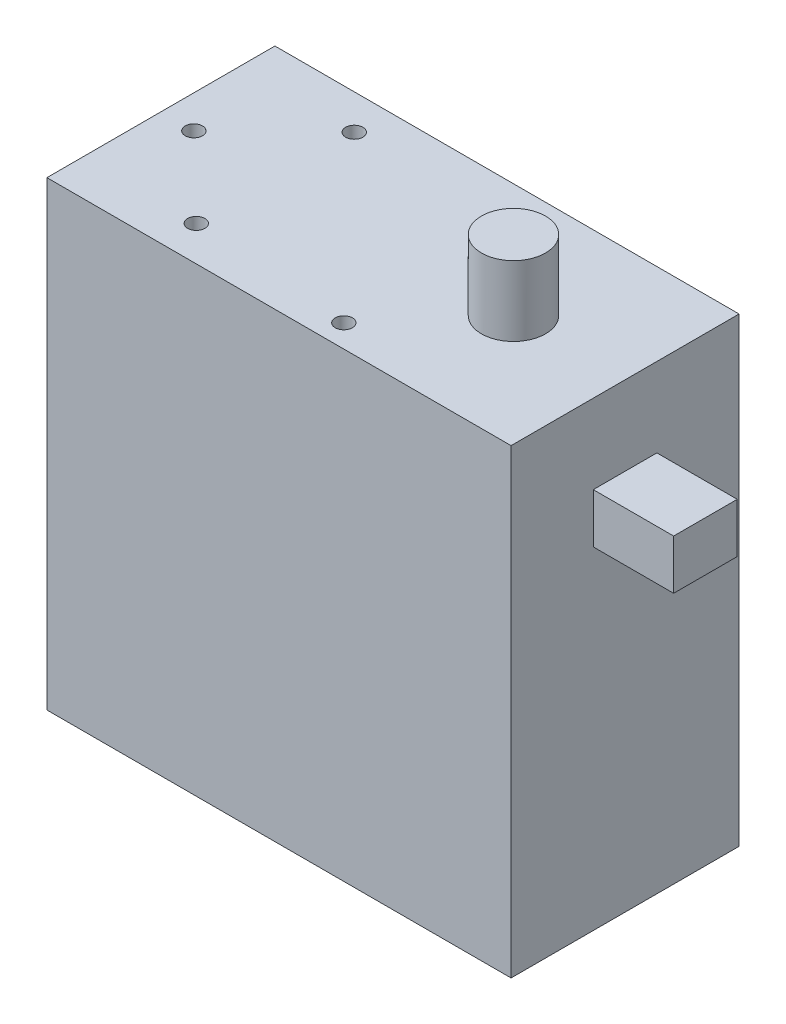
SolidWorks part; units mm, degrees
ref_plane "Front Plane" through (0, 0, 0) normal (0, 0, 1) x (1, 0, 0)
ref_plane "Top Plane" through (0, 0, 0) normal (0, 1, 0) x (1, 0, 0)
ref_plane "Right Plane" through (0, 0, 0) normal (1, 0, 0) x (0, 0, -1)
sketch "Sketch1" plane through (0, 0, 0) normal (0, 0, 1) x (1, 0, 0)
  line L1 (0, 0) -> (40.43, 0)
  line L2 (0, 0) -> (0, 40.16)
  line L3 (0, 40.16) -> (40.43, 40.16)
  line L4 (40.43, 0) -> (40.43, 40.16)
  dimension "D1" = 40.16
  dimension "D2" = 40.43
extrude "ServoBody" add sketch "Sketch1" along normal blind 19.86
sketch "Sketch2" plane through (0, 40.16, 0) normal (0, 1, 0) x (1, 0, 0)
  line L0 (40.43, -19.86) -> (40.43, 0) construction
  circle A0 centre (30.71, -9.93) radius 2.79
  point P4 (0, 0)
  point P5 (40.43, -9.93)
  dimension "D1" = 5.58
  dimension "D2" = 9.72
extrude "GearHinge" add sketch "Sketch2" along normal blind 6.1
sketch "Sketch3" plane through (0, 0, 0) normal (0, -1, 0) x (1, 0, 0)
  circle A0 centre (30.71, 9.93) radius 3.01
  circle A1 centre (30.71, 9.93) radius 2.79 construction
  dimension "D1" = 6.02
extrude "SmoothHinge" add sketch "Sketch3" along normal blind 5.5
sketch "Sketch4" plane through (0, 40.16, 0) normal (0, 1, 0) x (1, 0, 0)
  line L0 (40.43, -19.86) -> (40.43, 0) construction
  line L1 (40.43, 0) -> (0, 0) construction
  line L2 (40.43, -19.86) -> (0, -19.86) construction
  line L3 (0, -19.86) -> (0, 0) construction
  circle A0 centre (23.88, -1.98) radius 0.75
  circle A4 centre (23.88, -17.88) radius 0.75
  circle A5 centre (2.87, -9.93) radius 0.75
  circle A6 centre (9.96, -3.05) radius 0.75
  circle A7 centre (9.96, -16.81) radius 0.75
  point P14 (0, 0)
  point P15 (0, 0)
  point P18 (0, 0)
  point P21 (0, -9.93)
  dimension "D1" = 1.5
  dimension "D4" = 1.98
  dimension "D2" = 16.55
  dimension "D3" = 1.98
  dimension "D5" = 3.05
  dimension "D6" = 3.05
  dimension "D7" = 13.92
  dimension "D8" = 2.87
extrude "GearScrewHoles" cut sketch "Sketch4" against normal blind 2
sketch "Sketch5" plane through (0, 0, 0) normal (0, -1, 0) x (1, 0, 0)
  line L0 (40.43, 19.86) -> (40.43, 0) construction
  line L1 (0, 19.86) -> (40.43, 19.86) construction
  line L3 (0, 0) -> (40.43, 0) construction
  circle A0 centre (17.31, 17.86) radius 0.75
  circle A1 centre (38.43, 17.86) radius 0.75
  circle A2 centre (2.07, 17.86) radius 0.75
  circle A3 centre (17.31, 2) radius 0.75
  circle A4 centre (38.43, 2) radius 0.75
  circle A5 centre (2.07, 2) radius 0.75
  point P16 (0, 0)
  point P17 (0, 0)
  dimension "D1" = 1.5
  dimension "D2" = 21.12
  dimension "D3" = 2
  dimension "D4" = 2
  dimension "D5" = 15.24
  dimension "D6" = 2
extrude "SmoothScrewHoles" cut sketch "Sketch5" against normal blind 2
sketch "Sketch6" plane through (40.43, 0, 0) normal (1, 0, 0) x (0, 0, -1)
  line L0 (-19.86, 40.16) -> (0, 40.16) construction
  line L1 (-12.7, 33.26) -> (-7.16, 33.26)
  line L2 (-12.7, 33.26) -> (-12.7, 28.94)
  line L3 (-12.7, 28.94) -> (-7.16, 28.94)
  line L4 (-7.16, 33.26) -> (-7.16, 28.94)
  point P6 (-9.93, 33.26)
  point P7 (-9.93, 40.16)
  dimension "D1" = 6.9
  dimension "D2" = 5.54
  dimension "D3" = 4.32
extrude "Cable" add sketch "Sketch6" along normal blind 7
